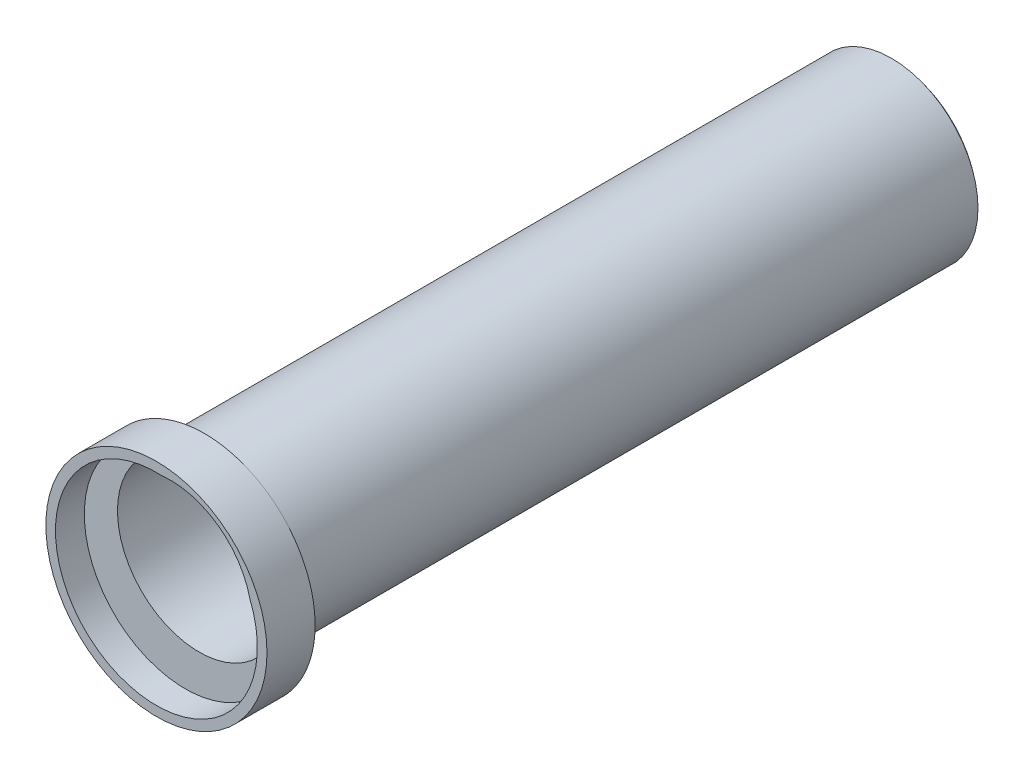
SolidWorks part; units mm, degrees
ref_plane "前视基准面" through (0, 0, 0) normal (0, 0, 1) x (1, 0, 0)
ref_plane "上视基准面" through (0, 0, 0) normal (0, 1, 0) x (1, 0, 0)
ref_plane "右视基准面" through (0, 0, 0) normal (1, 0, 0) x (0, 0, -1)
sketch "Sketch1" plane through (0, 0, 0) normal (0, 0, 1) x (1, 0, 0)
  circle A0 centre (0, 0) radius 23
  dimension "D1" = 46
extrude "Boss-Extrude1" add sketch "Sketch1" along normal blind 10
sketch "Sketch2" plane through (0, 0, 0) normal (0, 0, -1) x (-1, 0, 0)
  circle A0 centre (-2.9, 4.07) radius 18
  dimension "D1" = 2.9
  dimension "D2" = 4.07
extrude "Boss-Extrude2" add sketch "Sketch2" along normal blind 140
sketch "Sketch3" plane through (0, 0, 10) normal (0, 0, 1) x (1, 0, 0)
  circle A0 centre (0, 0) radius 21
extrude "Cut-Extrude1" cut sketch "Sketch3" against normal blind 6
sketch "Sketch4" plane through (0, 0, 4) normal (0, 0, 1) x (1, 0, 0)
  circle A0 centre (2.9, 4.07) radius 17
extrude "Cut-Extrude2" cut sketch "Sketch4" against normal blind 143
sketch "Sketch5" plane through (0, 0, 4) normal (0, 0, 1) x (1, 0, 0)
  circle A0 centre (2.9, 4.07) radius 17
extrude "Cut-Extrude3" cut sketch "Sketch5" along normal blind 10
ref_plane "Plane1" through (0, 4.07, 0) normal (0, 1, 0) x (1, 0, 0)
sketch "Sketch6" plane through (0, 4.07, 0) normal (0, 1, 0) x (1, 0, 0)
  line L0 (2.9, 149.3932) -> (2.9, 124.3891) construction
  line L1 (2.9, 142.9215) -> (-7.1, 142.9215)
  line L2 (2.9, 142.9215) -> (2.9, 140)
  line L3 (20.9, 140) -> (-15.1, 140) construction
  line L4 (2.9, 140) -> (-15.1, 140)
  arc A0 (-7.1, 142.9215) -> (-15.1, 140) centre (-7.2707, 130.975) ccw
  dimension "D1" = 10
revolve "Revolve1" add sketch "Sketch6" angle 360 about L0
